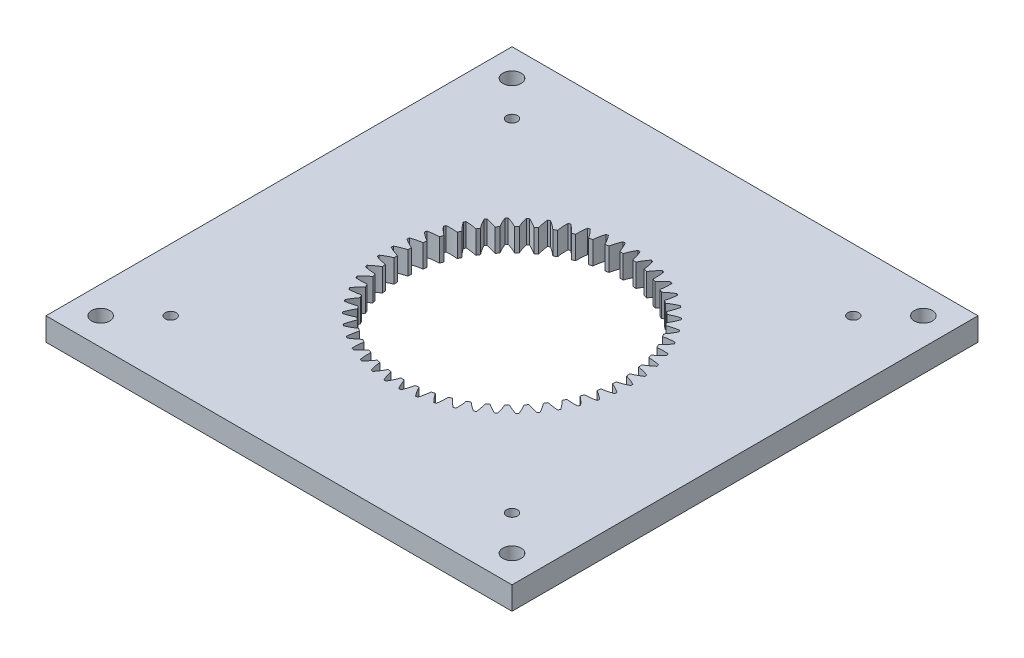
SolidWorks part; units mm, degrees
ref_plane "Front Plane" through (0, 0, 0) normal (0, 0, 1) x (1, 0, 0)
ref_plane "Top Plane" through (0, 0, 0) normal (0, 1, 0) x (1, 0, 0)
ref_plane "Right Plane" through (0, 0, 0) normal (1, 0, 0) x (0, 0, -1)
sketch "Sketch1" plane through (0, 0, 0) normal (0, 1, 0) x (1, 0, 0)
  line L1 (-50.8, -50.8) -> (50.8, -50.8)
  line L2 (-50.8, -50.8) -> (-50.8, 50.8)
  line L3 (-50.8, 50.8) -> (50.8, 50.8)
  line L4 (50.8, -50.8) -> (50.8, 50.8)
  line L5 (-50.8, -50.8) -> (50.8, 50.8) construction
  line L6 (-50.8, 50.8) -> (50.8, -50.8) construction
  point P0 (0, 0)
  dimension "D1" = 101.6
  dimension "D2" = 101.6
extrude "Boss-Extrude1" add sketch "Sketch1" along normal blind 5
extrude "Cut-Extrude2" cut sketch "Sketch3" against normal through all contours A212 A213 A207 A206 A208 A209 A203 A202 A204 A205 A199 A198 A200 A201 A195 A194 A196 A197 A191 A190 A192 A193 A187 A186 A188 A189 A183 A182 A184 A185 A179 A178 A180 A181 A175 A174 A176 A177 A171 A170 A172 A173 A167 A166 A168 A169 A163 A162 A164 A165 A159
sketch "Sketch3" plane through (-15.1201, 10, -90.8815) normal (0, 1, 0) x (1, 0, 0)
  line L0 (15.1201, -90.8815) -> (16.1521, -67.733) construction
  line L1 (15.1201, -90.8815) -> (19.0452, -68.0448) construction
  arc A10 (6.6825, -68.5493) -> (5.9834, -68.8261) centre (15.1201, -90.8815) ccw
  arc A11 (6.8367, -66.0343) -> (6.6825, -68.5493) centre (19.0452, -68.0448) ccw
  arc A12 (5.9834, -68.8261) -> (4.2099, -67.1448) centre (-3.3739, -76.9212) ccw
  arc A13 (4.2099, -67.1448) -> (3.7164, -67.378) centre (15.1201, -90.8815) ccw
  arc A18 (1.3209, -68.6994) -> (0.8605, -68.9926) centre (15.1201, -90.8815) ccw
  arc A19 (3.2912, -70.1451) -> (1.3209, -68.6994) centre (-4.9778, -79.3492) ccw
  arc A20 (3.9501, -69.7829) -> (3.2912, -70.1451) centre (15.1201, -90.8815) ccw
  arc A21 (3.7878, -67.2685) -> (3.9501, -69.7829) centre (16.1521, -67.733) ccw
  arc A22 (9.548, -67.6679) -> (8.8198, -67.8549) centre (15.1201, -90.8815) ccw
  arc A23 (10.0162, -65.1921) -> (9.548, -67.6679) centre (21.8765, -68.7169) ccw
  arc A24 (8.8198, -67.8549) -> (7.2709, -65.9646) centre (-1.4784, -74.7134) ccw
  arc A25 (7.2709, -65.9646) -> (6.752, -66.134) centre (15.1201, -90.8815) ccw
  arc A26 (12.5014, -67.1526) -> (11.7554, -67.2468) centre (15.1201, -90.8815) ccw
  arc A27 (13.2762, -64.755) -> (12.5014, -67.1526) centre (24.6012, -69.7384) ccw
  arc A28 (11.7554, -67.2468) -> (10.4557, -65.1773) centre (0.6789, -72.7605) ccw
  arc A29 (10.4557, -65.1773) -> (9.9197, -65.2804) centre (15.1201, -90.8815) ccw
  arc A30 (15.4961, -67.0115) -> (14.7442, -67.0115) centre (15.1201, -90.8815) ccw
  arc A31 (16.5652, -64.7299) -> (15.4961, -67.0115) centre (27.1764, -71.0934) ccw
  arc A32 (14.7442, -67.0115) -> (13.7141, -64.7954) centre (3.0639, -71.0934) ccw
  arc A33 (13.7141, -64.7954) -> (13.1694, -64.8304) centre (15.1201, -90.8815) ccw
  arc A34 (18.4848, -67.2468) -> (17.7389, -67.1526) centre (15.1201, -90.8815) ccw
  arc A35 (19.8315, -65.1172) -> (18.4848, -67.2468) centre (29.5614, -72.7605) ccw
  arc A36 (17.7389, -67.1526) -> (16.9946, -64.8248) centre (5.6391, -69.7384) ccw
  arc A37 (16.9946, -64.8248) -> (16.4498, -64.7914) centre (15.1201, -90.8815) ccw
  arc A38 (21.4205, -67.8549) -> (20.6922, -67.6679) centre (15.1201, -90.8815) ccw
  arc A39 (23.0235, -65.9108) -> (21.4205, -67.8549) centre (31.7187, -74.7134) ccw
  arc A40 (20.6922, -67.6679) -> (20.2456, -65.2652) centre (8.3638, -68.7169) ccw
  arc A41 (20.2456, -65.2652) -> (19.7093, -65.1638) centre (15.1201, -90.8815) ccw
  arc A42 (24.2568, -68.8261) -> (23.5577, -68.5493) centre (15.1201, -90.8815) ccw
  arc A43 (26.0908, -67.0983) -> (24.2568, -68.8261) centre (33.6142, -76.9212) ccw
  arc A44 (23.5577, -68.5493) -> (23.4157, -66.1096) centre (11.195, -68.0448) ccw
  arc A45 (23.4157, -66.1096) -> (22.8964, -65.9417) centre (15.1201, -90.8815) ccw
  arc A46 (26.9491, -70.1451) -> (26.2902, -69.7829) centre (15.1201, -90.8815) ccw
  arc A47 (28.9851, -68.6608) -> (26.9491, -70.1451) centre (35.2181, -79.3492) ccw
  arc A48 (26.2902, -69.7829) -> (26.4551, -67.3447) centre (14.0882, -67.733) ccw
  arc A49 (26.4551, -67.3447) -> (25.9609, -67.113) centre (15.1201, -90.8815) ccw
  arc A50 (29.4547, -71.7912) -> (28.8464, -71.3493) centre (15.1201, -90.8815) ccw
  arc A51 (31.6608, -70.5738) -> (29.4547, -71.7912) centre (36.505, -81.9591) ccw
  arc A52 (28.8464, -71.3493) -> (29.3156, -68.9509) centre (16.9976, -67.7862) ccw
  arc A53 (29.3156, -68.9509) -> (28.8544, -68.6591) centre (15.1201, -90.8815) ccw
  arc A54 (31.7344, -73.7384) -> (31.1862, -73.2236) centre (15.1201, -90.8815) ccw
  arc A55 (34.0756, -72.807) -> (31.7344, -73.7384) centre (37.4546, -84.7097) ccw
  arc A56 (31.1862, -73.2236) -> (31.9523, -70.903) centre (19.8774, -68.2036) ccw
  arc A57 (31.9523, -70.903) -> (31.5313, -70.5557) centre (15.1201, -90.8815) ccw
  arc A58 (33.752, -75.9558) -> (33.2727, -75.3765) centre (15.1201, -90.8815) ccw
  arc A59 (36.1915, -75.3253) -> (33.752, -75.9558) centre (38.052, -87.5576) ccw
  arc A60 (33.2727, -75.3765) -> (34.3236, -73.1702) centre (22.6822, -68.9786) ccw
  arc A61 (34.3236, -73.1702) -> (33.9494, -72.7729) centre (15.1201, -90.8815) ccw
  arc A62 (35.4757, -78.4087) -> (35.0728, -77.7739) centre (15.1201, -90.8815) ccw
  arc A63 (37.975, -78.0889) -> (35.4757, -78.4087) centre (38.2878, -90.4579) ccw
  arc A64 (35.0728, -77.7739) -> (36.392, -75.7167) centre (25.3677, -70.0991) ccw
  arc A65 (36.392, -75.7167) -> (36.0705, -75.2756) centre (15.1201, -90.8815) ccw
  arc A66 (36.8785, -81.0583) -> (36.5583, -80.378) centre (15.1201, -90.8815) ccw
  arc A67 (39.3981, -81.0542) -> (36.8785, -81.0583) centre (38.1582, -93.365) ccw
  arc A68 (36.5583, -80.378) -> (38.1249, -78.5023) centre (27.8916, -71.5474) ccw
  arc A69 (38.1249, -78.5023) -> (37.8613, -78.0244) centre (15.1201, -90.8815) ccw
  arc A70 (37.9381, -83.8628) -> (37.7057, -83.1477) centre (15.1201, -90.8815) ccw
  arc A71 (40.4384, -84.1746) -> (37.9381, -83.8628) centre (37.6653, -96.2328) ccw
  arc A72 (37.7057, -83.1477) -> (39.495, -81.4832) centre (30.2141, -73.3005) ccw
  arc A73 (39.495, -81.4832) -> (39.2934, -80.976) centre (15.1201, -90.8815) ccw
  arc A74 (38.6378, -86.778) -> (38.4969, -86.0394) centre (15.1201, -90.8815) ccw
  arc A75 (41.0794, -87.4007) -> (38.6378, -86.778) centre (36.8168, -99.0163) ccw
  arc A76 (38.4969, -86.0394) -> (40.4807, -84.6123) centre (32.2986, -75.3309) ccw
  arc A77 (40.4807, -84.6123) -> (40.3442, -84.0838) centre (15.1201, -90.8815) ccw
  arc A78 (38.9667, -89.7579) -> (38.9195, -89.0075) centre (15.1201, -90.8815) ccw
  arc A79 (41.3109, -90.6817) -> (38.9667, -89.7579) centre (35.6262, -101.6714) ccw
  arc A80 (38.9195, -89.0075) -> (41.0665, -87.8402) centre (34.1121, -77.6066) ccw
  arc A81 (41.0665, -87.8402) -> (40.9973, -87.2989) centre (15.1201, -90.8815) ccw
  arc A82 (38.9195, -92.7555) -> (38.9667, -92.0051) centre (15.1201, -90.8815) ccw
  arc A83 (41.1294, -93.9658) -> (38.9195, -92.7555) centre (34.1121, -104.1564) ccw
  arc A84 (38.9667, -92.0051) -> (41.2431, -91.1162) centre (35.6262, -80.0916) ccw
  arc A85 (41.2431, -91.1162) -> (41.2423, -90.5704) centre (15.1201, -90.8815) ccw
  arc A86 (38.4969, -95.7236) -> (38.6378, -94.985) centre (15.1201, -90.8815) ccw
  arc A87 (40.5378, -97.2013) -> (38.4969, -95.7236) centre (32.2986, -106.4321) ccw
  arc A88 (38.6378, -94.985) -> (41.0077, -94.3884) centre (36.8168, -82.7468) ccw
  arc A89 (41.0077, -94.3884) -> (41.0753, -93.8468) centre (15.1201, -90.8815) ccw
  arc A90 (37.7057, -98.6153) -> (37.9381, -97.9002) centre (15.1201, -90.8815) ccw
  arc A91 (39.5453, -100.3372) -> (37.7057, -98.6153) centre (30.2141, -108.4625) ccw
  arc A92 (37.9381, -97.9002) -> (40.364, -97.6053) centre (37.6653, -85.5302) ccw
  arc A93 (40.364, -97.6053) -> (40.499, -97.0765) centre (15.1201, -90.8815) ccw
  arc A94 (36.5583, -101.385) -> (36.8785, -100.7047) centre (15.1201, -90.8815) ccw
  arc A95 (38.1676, -103.3239) -> (36.5583, -101.385) centre (27.8916, -110.2157) ccw
  arc A96 (36.8785, -100.7047) -> (39.3222, -100.7162) centre (38.1582, -88.3981) ccw
  arc A97 (39.3222, -100.7162) -> (39.5224, -100.2084) centre (15.1201, -90.8815) ccw
  arc A98 (35.0728, -103.9891) -> (35.4757, -103.3543) centre (15.1201, -90.8815) ccw
  arc A99 (36.4264, -106.1144) -> (35.0728, -103.9891) centre (25.3677, -111.6639) ccw
  arc A100 (35.4757, -103.3543) -> (37.8988, -103.672) centre (38.2878, -91.3051) ccw
  arc A101 (37.8988, -103.672) -> (38.161, -103.1933) centre (15.1201, -90.8815) ccw
  arc A102 (33.2727, -106.3865) -> (33.752, -105.8072) centre (15.1201, -90.8815) ccw
  arc A103 (34.3492, -108.6647) -> (33.2727, -106.3865) centre (22.6822, -112.7844) ccw
  arc A104 (33.752, -105.8072) -> (36.1161, -106.426) centre (38.052, -94.2054) ccw
  arc A105 (36.1161, -106.426) -> (36.4363, -105.984) centre (15.1201, -90.8815) ccw
  arc A106 (31.1862, -108.5394) -> (31.7344, -108.0247) centre (15.1201, -90.8815) ccw
  arc A107 (31.9687, -110.9345) -> (31.1862, -108.5394) centre (19.8774, -113.5594) ccw
  arc A108 (31.7344, -108.0247) -> (34.0023, -108.935) centre (37.4546, -97.0533) ccw
  arc A109 (34.0023, -108.935) -> (34.3753, -108.5366) centre (15.1201, -90.8815) ccw
  arc A110 (28.8464, -110.4138) -> (29.4547, -109.9718) centre (15.1201, -90.8815) ccw
  arc A111 (29.3226, -112.888) -> (28.8464, -110.4138) centre (16.9976, -113.9769) ccw
  arc A112 (29.4547, -109.9718) -> (31.5907, -111.1592) centre (36.505, -99.8039) ccw
  arc A113 (31.5907, -111.1592) -> (32.0107, -110.8107) centre (15.1201, -90.8815) ccw
  arc A114 (26.2902, -111.9801) -> (26.9491, -111.6179) centre (15.1201, -90.8815) ccw
  arc A115 (26.4524, -114.4946) -> (26.2902, -111.9801) centre (14.0882, -114.0301) ccw
  arc A116 (26.9491, -111.6179) -> (28.9194, -113.0636) centre (35.2181, -102.4138) ccw
  arc A117 (28.9194, -113.0636) -> (29.3798, -112.7705) centre (15.1201, -90.8815) ccw
  arc A118 (23.5577, -113.2137) -> (24.2568, -112.9369) centre (15.1201, -90.8815) ccw
  arc A119 (23.4036, -115.7287) -> (23.5577, -113.2137) centre (11.195, -113.7182) ccw
  arc A120 (24.2568, -112.9369) -> (26.0304, -114.6182) centre (33.6142, -104.8418) ccw
  arc A121 (26.0304, -114.6182) -> (26.5239, -114.3851) centre (15.1201, -90.8815) ccw
  arc A122 (20.6922, -114.0951) -> (21.4205, -113.9081) centre (15.1201, -90.8815) ccw
  arc A123 (20.2241, -116.5709) -> (20.6922, -114.0951) centre (8.3638, -113.0462) ccw
  arc A124 (21.4205, -113.9081) -> (22.9694, -115.7984) centre (31.7187, -107.0496) ccw
  arc A125 (22.9694, -115.7984) -> (23.4882, -115.629) centre (15.1201, -90.8815) ccw
  arc A126 (17.7389, -114.6104) -> (18.4848, -114.5162) centre (15.1201, -90.8815) ccw
  arc A127 (16.9641, -117.0081) -> (17.7389, -114.6104) centre (5.6391, -112.0246) ccw
  arc A128 (18.4848, -114.5162) -> (19.7846, -116.5857) centre (29.5614, -109.0025) ccw
  arc A129 (19.7846, -116.5857) -> (20.3205, -116.4827) centre (15.1201, -90.8815) ccw
  arc A130 (14.7442, -114.7515) -> (15.4961, -114.7515) centre (15.1201, -90.8815) ccw
  arc A131 (13.675, -117.0332) -> (14.7442, -114.7515) centre (3.0639, -110.6696) ccw
  arc A132 (15.4961, -114.7515) -> (16.5262, -116.9676) centre (27.1764, -110.6696) ccw
  arc A133 (16.5262, -116.9676) -> (17.0709, -116.9326) centre (15.1201, -90.8815) ccw
  arc A134 (11.7554, -114.5162) -> (12.5014, -114.6104) centre (15.1201, -90.8815) ccw
  arc A135 (10.4088, -116.6458) -> (11.7554, -114.5162) centre (0.6789, -109.0025) ccw
  arc A136 (12.5014, -114.6104) -> (13.2457, -116.9382) centre (24.6012, -112.0246) ccw
  arc A137 (13.2457, -116.9382) -> (13.7904, -116.9716) centre (15.1201, -90.8815) ccw
  arc A138 (8.8198, -113.9081) -> (9.548, -114.0951) centre (15.1201, -90.8815) ccw
  arc A139 (7.2168, -115.8522) -> (8.8198, -113.9081) centre (-1.4784, -107.0496) ccw
  arc A140 (9.548, -114.0951) -> (9.9947, -116.4978) centre (21.8765, -113.0462) ccw
  arc A141 (9.9947, -116.4978) -> (10.5309, -116.5993) centre (15.1201, -90.8815) ccw
  arc A142 (5.9834, -112.9369) -> (6.6825, -113.2137) centre (15.1201, -90.8815) ccw
  arc A143 (4.1495, -114.6647) -> (5.9834, -112.9369) centre (-3.3739, -104.8418) ccw
  arc A144 (6.6825, -113.2137) -> (6.8245, -115.6534) centre (19.0452, -113.7182) ccw
  arc A145 (6.8245, -115.6534) -> (7.3438, -115.8213) centre (15.1201, -90.8815) ccw
  arc A146 (3.2912, -111.6179) -> (3.9501, -111.9801) centre (15.1201, -90.8815) ccw
  arc A147 (1.2551, -113.1022) -> (3.2912, -111.6179) centre (-4.9778, -102.4138) ccw
  arc A148 (3.9501, -111.9801) -> (3.7852, -114.4183) centre (16.1521, -114.0301) ccw
  arc A149 (3.7852, -114.4183) -> (4.2794, -114.65) centre (15.1201, -90.8815) ccw
  arc A150 (0.7855, -109.9718) -> (1.3938, -110.4138) centre (15.1201, -90.8815) ccw
  arc A151 (-1.4205, -111.1892) -> (0.7855, -109.9718) centre (-6.2647, -99.8039) ccw
  arc A152 (1.3938, -110.4138) -> (0.9246, -112.8121) centre (13.2427, -113.9769) ccw
  arc A153 (0.9246, -112.8121) -> (1.3859, -113.1039) centre (15.1201, -90.8815) ccw
  arc A154 (-1.4941, -108.0247) -> (-0.946, -108.5394) centre (15.1201, -90.8815) ccw
  arc A155 (-3.8353, -108.956) -> (-1.4941, -108.0247) centre (-7.2143, -97.0533) ccw
  arc A156 (-0.946, -108.5394) -> (-1.7121, -110.86) centre (10.3629, -113.5594) ccw
  arc A157 (-1.7121, -110.86) -> (-1.291, -111.2073) centre (15.1201, -90.8815) ccw
  arc A158 (-3.5117, -105.8072) -> (-3.0324, -106.3865) centre (15.1201, -90.8815) ccw
  arc A159 (-5.9512, -106.4377) -> (-3.5117, -105.8072) centre (-7.8118, -94.2054) ccw
  arc A160 (-3.0324, -106.3865) -> (-4.0833, -108.5928) centre (7.5581, -112.7844) ccw
  arc A161 (-4.0833, -108.5928) -> (-3.7091, -108.9901) centre (15.1201, -90.8815) ccw
  arc A162 (-5.2355, -103.3543) -> (-4.8326, -103.9891) centre (15.1201, -90.8815) ccw
  arc A163 (-7.7348, -103.6741) -> (-5.2355, -103.3543) centre (-8.0475, -91.3051) ccw
  arc A164 (-4.8326, -103.9891) -> (-6.1517, -106.0463) centre (4.8726, -111.6639) ccw
  arc A165 (-6.1517, -106.0463) -> (-5.8303, -106.4874) centre (15.1201, -90.8815) ccw
  arc A166 (-6.6382, -100.7047) -> (-6.3181, -101.385) centre (15.1201, -90.8815) ccw
  arc A167 (-9.1579, -100.7088) -> (-6.6382, -100.7047) centre (-7.9179, -88.3981) ccw
  arc A168 (-6.3181, -101.385) -> (-7.8846, -103.2607) centre (2.3486, -110.2157) ccw
  arc A169 (-7.8846, -103.2607) -> (-7.621, -103.7386) centre (15.1201, -90.8815) ccw
  arc A170 (-7.6978, -97.9002) -> (-7.4654, -98.6153) centre (15.1201, -90.8815) ccw
  arc A171 (-10.1981, -97.5884) -> (-7.6978, -97.9002) centre (-7.425, -85.5302) ccw
  arc A172 (-7.4654, -98.6153) -> (-9.2548, -100.2798) centre (0.0261, -108.4625) ccw
  arc A173 (-9.2548, -100.2798) -> (-9.0531, -100.787) centre (15.1201, -90.8815) ccw
  arc A174 (-8.3975, -94.985) -> (-8.2567, -95.7236) centre (15.1201, -90.8815) ccw
  arc A175 (-10.8391, -94.3623) -> (-8.3975, -94.985) centre (-6.5766, -82.7468) ccw
  arc A176 (-8.2567, -95.7236) -> (-10.2405, -97.1507) centre (-2.0583, -106.4321) ccw
  arc A177 (-10.2405, -97.1507) -> (-10.104, -97.6792) centre (15.1201, -90.8815) ccw
  arc A178 (-8.7264, -92.0051) -> (-8.6792, -92.7555) centre (15.1201, -90.8815) ccw
  arc A179 (-11.0707, -91.0813) -> (-8.7264, -92.0051) centre (-5.3859, -80.0916) ccw
  arc A180 (-8.6792, -92.7555) -> (-10.8262, -93.9228) centre (-3.8719, -104.1564) ccw
  arc A181 (-10.8262, -93.9228) -> (-10.757, -94.4642) centre (15.1201, -90.8815) ccw
  arc A182 (-8.6792, -89.0075) -> (-8.7264, -89.7579) centre (15.1201, -90.8815) ccw
  arc A183 (-10.8892, -87.7972) -> (-8.6792, -89.0075) centre (-3.8719, -77.6066) ccw
  arc A184 (-8.7264, -89.7579) -> (-11.0028, -90.6468) centre (-5.3859, -101.6714) ccw
  arc A185 (-11.0028, -90.6468) -> (-11.002, -91.1926) centre (15.1201, -90.8815) ccw
  arc A186 (-8.2567, -86.0394) -> (-8.3975, -86.778) centre (15.1201, -90.8815) ccw
  arc A187 (-10.2975, -84.5617) -> (-8.2567, -86.0394) centre (-2.0583, -75.3309) ccw
  arc A188 (-8.3975, -86.778) -> (-10.7674, -87.3746) centre (-6.5766, -99.0163) ccw
  arc A189 (-10.7674, -87.3746) -> (-10.835, -87.9162) centre (15.1201, -90.8815) ccw
  arc A190 (-7.4654, -83.1477) -> (-7.6978, -83.8628) centre (15.1201, -90.8815) ccw
  arc A191 (-9.305, -81.4258) -> (-7.4654, -83.1477) centre (0.0261, -73.3005) ccw
  arc A192 (-7.6978, -83.8628) -> (-10.1238, -84.1577) centre (-7.425, -96.2328) ccw
  arc A193 (-10.1238, -84.1577) -> (-10.2587, -84.6865) centre (15.1201, -90.8815) ccw
  arc A194 (-6.3181, -80.378) -> (-6.6382, -81.0583) centre (15.1201, -90.8815) ccw
  arc A195 (-7.9273, -78.4391) -> (-6.3181, -80.378) centre (2.3486, -71.5474) ccw
  arc A196 (-6.6382, -81.0583) -> (-9.082, -81.0468) centre (-7.9179, -93.365) ccw
  arc A197 (-9.082, -81.0468) -> (-9.2822, -81.5546) centre (15.1201, -90.8815) ccw
  arc A198 (-4.8326, -77.7739) -> (-5.2355, -78.4087) centre (15.1201, -90.8815) ccw
  arc A199 (-6.1861, -75.6486) -> (-4.8326, -77.7739) centre (4.8726, -70.0991) ccw
  arc A200 (-5.2355, -78.4087) -> (-7.6585, -78.091) centre (-8.0475, -90.4579) ccw
  arc A201 (-7.6585, -78.091) -> (-7.9208, -78.5697) centre (15.1201, -90.8815) ccw
  arc A202 (-3.0324, -75.3765) -> (-3.5117, -75.9558) centre (15.1201, -90.8815) ccw
  arc A203 (-4.1089, -73.0984) -> (-3.0324, -75.3765) centre (7.5581, -68.9786) ccw
  arc A204 (-3.5117, -75.9558) -> (-5.8758, -75.337) centre (-7.8118, -87.5576) ccw
  arc A205 (-5.8758, -75.337) -> (-6.196, -75.779) centre (15.1201, -90.8815) ccw
  arc A206 (-0.946, -73.2236) -> (-1.4941, -73.7384) centre (15.1201, -90.8815) ccw
  arc A207 (-1.7285, -70.8285) -> (-0.946, -73.2236) centre (10.3629, -68.2036) ccw
  arc A208 (-1.4941, -73.7384) -> (-3.762, -72.8281) centre (-7.2143, -84.7097) ccw
  arc A209 (-3.762, -72.8281) -> (-4.1351, -73.2265) centre (15.1201, -90.8815) ccw
  arc A210 (1.3938, -71.3493) -> (0.7855, -71.7912) centre (15.1201, -90.8815) ccw
  arc A211 (0.9177, -68.875) -> (1.3938, -71.3493) centre (13.2427, -67.7862) ccw
  arc A212 (0.7855, -71.7912) -> (-1.3505, -70.6039) centre (-6.2647, -81.9591) ccw
  arc A213 (-1.3505, -70.6039) -> (-1.7705, -70.9524) centre (15.1201, -90.8815) ccw
extrude "Cut-Extrude3" cut sketch "Sketch4" against normal blind 100
sketch "Sketch4" plane through (-15.1201, -5, -90.8815) normal (0, -1, 0) x (1, 0, 0)
  circle A3 centre (-29.7236, 135.7252) radius 1.9844
  circle A4 centre (52.3311, 128.0925) radius 1.1906
  circle A6 centre (-22.0909, 128.0925) radius 1.1906
  circle A7 centre (59.9638, 135.7252) radius 1.9844
  circle A8 centre (52.3311, 53.6705) radius 1.1906
  circle A9 centre (59.9638, 46.0378) radius 1.9844
  circle A10 centre (-22.0909, 53.6705) radius 1.1906
  circle A11 centre (-29.7236, 46.0378) radius 1.9844
  point P21 (15.1201, 90.8815)
